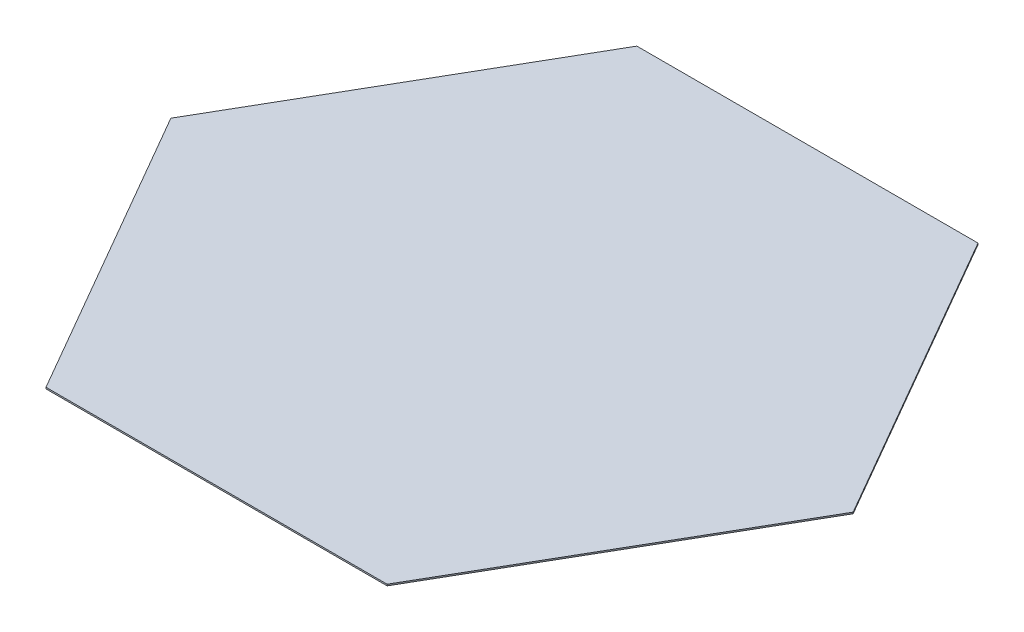
SolidWorks part; units mm, degrees
ref_plane "Front Plane" through (0, 0, 0) normal (0, 0, 1) x (1, 0, 0)
ref_plane "Top Plane" through (0, 0, 0) normal (0, 1, 0) x (1, 0, 0)
ref_plane "Right Plane" through (0, 0, 0) normal (1, 0, 0) x (0, 0, -1)
sketch "Sketch1" plane through (0, 0, 0) normal (0, 1, 0) x (1, 0, 0)
  line L1 (1154.7005, 0) -> (577.3503, 1000)
  line L2 (577.3503, 1000) -> (-577.3503, 1000)
  line L3 (-577.3503, 1000) -> (-1154.7005, 0)
  line L4 (-1154.7005, 0) -> (-577.3503, -1000)
  line L5 (-577.3503, -1000) -> (577.3503, -1000)
  line L6 (577.3503, -1000) -> (1154.7005, 0)
  circle A0 centre (0, 0) radius 1000 construction
  dimension "D1" = 2000
extrude "Boss-Extrude1" add sketch "Sketch1" along normal blind 5
